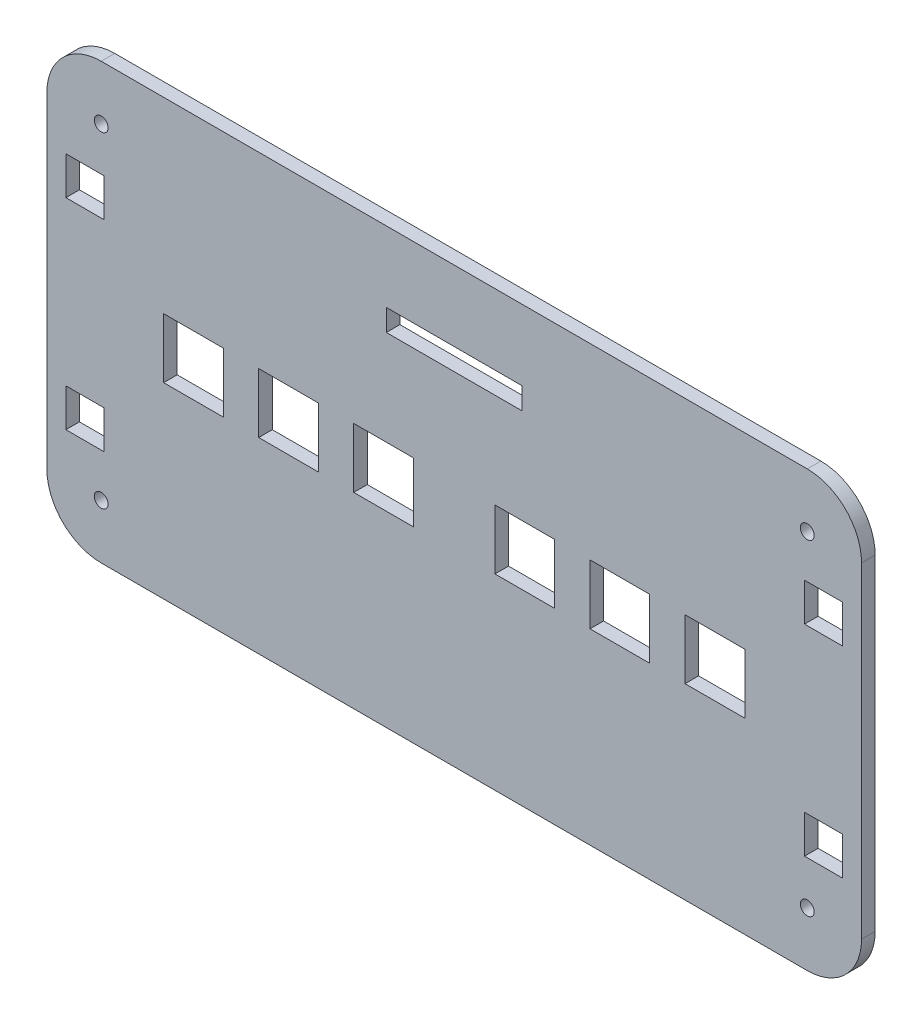
SolidWorks part; units mm, degrees
material "PMMA"
ref_plane "前视基准面" through (0, 0, 0) normal (0, 0, 1) x (1, 0, 0)
ref_plane "上视基准面" through (0, 0, 0) normal (0, 1, 0) x (1, 0, 0)
ref_plane "右视基准面" through (0, 0, 0) normal (1, 0, 0) x (0, 0, -1)
sketch "草图2" plane through (0, 0, 0) normal (0, 0, 1) x (1, 0, 0)
  line L0 (0, 1004.6496) -> (0, 4) construction
  line L10 (-72, -39) -> (-72, -61)
  line L11 (-37, -39) -> (-15, -39)
  line L19 (-22.1829, -50) -> (7.7078, -50) construction
  line L24 (37, -61) -> (15, -61)
  line L29 (15, -39) -> (15, -61)
  line L46 (129, -80) -> (143, -80)
  line L47 (-130, -130) -> (130, -130)
  line L48 (-150, -110) -> (-150, 10)
  line L49 (-130, 30) -> (130, 30)
  line L50 (150, -110) -> (150, 10)
  line L51 (0, 30) -> (0, 4) construction
  line L52 (-150, -50) -> (150, -50) construction
  line L53 (129, -6) -> (143, -6)
  line L58 (129, -6) -> (129, -20)
  line L59 (129, -20) -> (143, -20)
  line L60 (143, -6) -> (143, -20)
  line L65 (28.2222, 0) -> (37.5982, 0) construction
  line L66 (0, 0) -> (0, -130) construction
  line L67 (25, -4) -> (-25, -4)
  line L68 (25, -4) -> (25, 4)
  line L69 (25, 4) -> (-25, 4)
  line L70 (-25, -4) -> (-25, 4)
  line L71 (0, 0) -> (0, -4) construction
  line L72 (25, 0) -> (-25, 0) construction
  line L73 (0, 0) -> (0, -1009.2088) construction
  line L74 (136, -20) -> (136, -6) construction
  line L75 (129, -13) -> (143, -13) construction
  line L76 (143, -94) -> (143, -80)
  line L77 (129, -94) -> (143, -94)
  line L78 (129, -94) -> (129, -80)
  line L79 (-129, -94) -> (-129, -80)
  line L80 (-129, -94) -> (-143, -94)
  line L81 (-143, -94) -> (-143, -80)
  line L82 (-129, -80) -> (-143, -80)
  line L83 (-129, -20) -> (-143, -20)
  line L84 (-143, -6) -> (-143, -20)
  line L85 (-129, -6) -> (-143, -6)
  line L86 (-129, -6) -> (-129, -20)
  line L87 (-37, -39) -> (-37, -61)
  line L88 (-37, -61) -> (-15, -61)
  line L89 (-15, -39) -> (-15, -61)
  line L90 (-26, -61) -> (-26, -39) construction
  line L91 (-37, -50) -> (-15, -50) construction
  line L92 (-72, -39) -> (-50, -39)
  line L93 (-50, -39) -> (-50, -61)
  line L94 (-72, -61) -> (-50, -61)
  line L95 (-107, -39) -> (-107, -61)
  line L96 (-107, -39) -> (-85, -39)
  line L97 (-85, -39) -> (-85, -61)
  line L98 (-107, -61) -> (-85, -61)
  line L99 (37, -39) -> (15, -39)
  line L100 (37, -39) -> (37, -61)
  line L101 (72, -39) -> (50, -39)
  line L102 (50, -39) -> (50, -61)
  line L103 (72, -61) -> (50, -61)
  line L104 (72, -39) -> (72, -61)
  line L105 (107, -39) -> (85, -39)
  line L106 (85, -39) -> (85, -61)
  line L107 (107, -61) -> (85, -61)
  line L108 (107, -39) -> (107, -61)
  arc A0 (130, 30) -> (150, 10) centre (130, 10) cw
  arc A1 (150, -110) -> (130, -130) centre (130, -110) cw
  arc A2 (-130, -130) -> (-150, -110) centre (-130, -110) cw
  arc A3 (-150, 10) -> (-130, 30) centre (-130, 10) cw
  circle A5 centre (130, -110) radius 2.55
  circle A6 centre (130, 10) radius 2.55
  circle A7 centre (-130, -110) radius 2.55
  circle A8 centre (-130, 10) radius 2.55
  point P0 (0, 0)
  point P1 (0, 0)
  point P4 (-26, -50)
  point P38 (0, -50)
  point P40 (0, -50)
  point P41 (136, -13)
  point P61 (150, 30)
  point P64 (150, -130)
  point P70 (-150, 30)
  dimension "D15" = 20
  dimension "D16" = 5.1
  dimension "D17" = 5.1
  dimension "D18" = 5.1
  dimension "D19" = 5.1
  dimension "D20" = 30
  dimension "D3" = 22
  dimension "D4" = 22
  dimension "D5" = 15
  dimension "D6" = 50
  dimension "D7" = 8
  dimension "D8" = 3
  dimension "D10" = 300
  dimension "D11" = 160
  dimension "D12" = 14
  dimension "D13" = 14
  dimension "D14" = 7
  dimension "D22" = 50
extrude "凸台-拉伸1" add sketch "草图2" along normal blind 5
